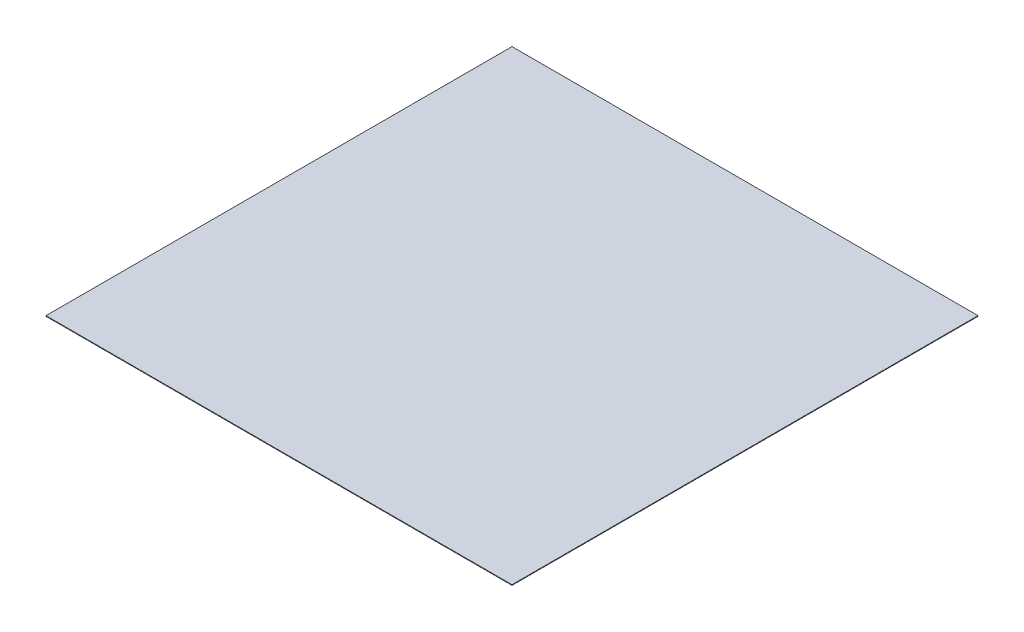
SolidWorks part; units mm, degrees
material "STYCAST 2850FT/Catalyst 23LV"
ref_plane "Front Plane" through (0, 0, 0) normal (0, 0, 1) x (1, 0, 0)
ref_plane "Top Plane" through (0, 0, 0) normal (0, 1, 0) x (1, 0, 0)
ref_plane "Right Plane" through (0, 0, 0) normal (1, 0, 0) x (0, 0, -1)
sketch "Sketch1" plane through (0, 0, 0) normal (0, 1, 0) x (1, 0, 0)
  line L1 (-95, -95) -> (95, -95)
  line L2 (-95, -95) -> (-95, 95)
  line L3 (-95, 95) -> (95, 95)
  line L4 (95, -95) -> (95, 95)
  line L5 (-95, -95) -> (95, 95) construction
  line L6 (-95, 95) -> (95, -95) construction
  point P0 (0, 0)
  dimension "D1" = 190
extrude "Boss-Extrude1" add sketch "Sketch1" along normal mid plane 0.25
equation "\"panel_width\"= 190mm"
equation "\"finger_joint_width\" = 50mm"
equation "\"D1@Sketch1\"=\"panel_width\""
